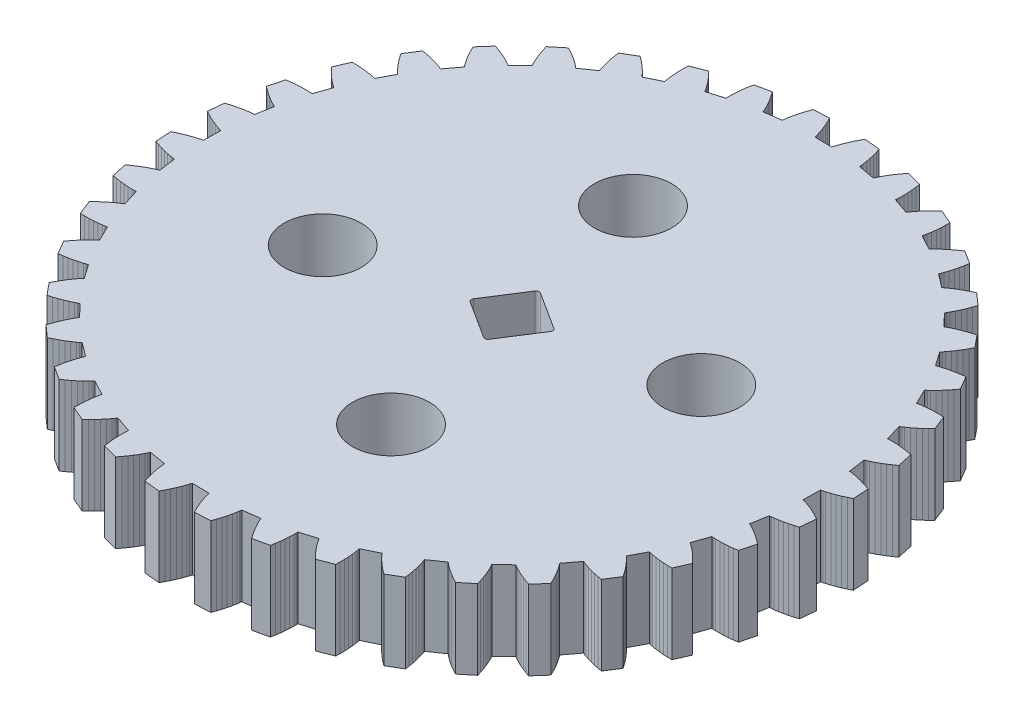
SolidWorks part; units mm, degrees
ref_plane "Front Plane" through (0, 0, 0) normal (0, 0, 1) x (1, 0, 0)
ref_plane "Top Plane" through (0, 0, 0) normal (0, 1, 0) x (1, 0, 0)
ref_plane "Right Plane" through (0, 0, 0) normal (1, 0, 0) x (0, 0, -1)
sketch "Sketch2" plane through (0, 0, 0) normal (0, 1, 0) x (1, 0, 0)
  line L0 (1.6245, 18.6336) -> (1.5605, 18.6409)
  line L1 (1.5605, 18.6409) -> (1.4964, 18.6492)
  line L2 (1.4964, 18.6492) -> (1.3679, 18.6686)
  line L3 (1.3679, 18.6686) -> (1.1102, 18.7172)
  line L4 (1.1102, 18.7172) -> (0.8515, 18.7777)
  line L5 (0.8515, 18.7777) -> (0.5922, 18.8492)
  line L6 (0.5922, 18.8492) -> (0.3324, 18.931)
  line L7 (0.3324, 18.931) -> (0.0723, 19.0226)
  line L8 (0.0723, 19.0226) -> (0.0134, 20.0093)
  line L9 (0.0134, 20.0093) -> (0.2607, 20.1312)
  line L10 (0.2607, 20.1312) -> (0.5089, 20.2434)
  line L11 (0.5089, 20.2434) -> (0.7578, 20.3453)
  line L12 (0.7578, 20.3453) -> (1.0074, 20.4362)
  line L13 (1.0074, 20.4362) -> (1.2576, 20.5151)
  line L14 (1.2576, 20.5151) -> (1.3828, 20.5496)
  line L15 (1.3828, 20.5496) -> (1.4455, 20.5655)
  line L16 (1.4455, 20.5655) -> (1.5081, 20.5804)
  line L17 (1.5081, 20.5804) -> (1.5283, 21.6521)
  line L18 (1.5283, 21.6521) -> (1.4663, 21.6694)
  line L19 (1.4663, 21.6694) -> (1.4043, 21.6877)
  line L20 (1.4043, 21.6877) -> (1.2804, 21.7268)
  line L21 (1.2804, 21.7268) -> (1.0334, 21.8151)
  line L22 (1.0334, 21.8151) -> (0.7874, 21.9154)
  line L23 (0.7874, 21.9154) -> (0.5425, 22.0266)
  line L24 (0.5425, 22.0266) -> (0.2987, 22.1481)
  line L25 (0.2987, 22.1481) -> (0.0561, 22.2792)
  line L26 (0.0561, 22.2792) -> (0.1523, 23.263)
  line L27 (0.1523, 23.263) -> (0.4156, 23.3447)
  line L28 (0.4156, 23.3447) -> (0.6783, 23.4167)
  line L29 (0.6783, 23.4167) -> (0.9401, 23.4783)
  line L30 (0.9401, 23.4783) -> (1.2009, 23.5291)
  line L31 (1.2009, 23.5291) -> (1.4603, 23.5679)
  line L32 (1.4603, 23.5679) -> (1.5894, 23.5824)
  line L33 (1.5894, 23.5824) -> (1.6537, 23.5883)
  line L34 (1.6537, 23.5883) -> (1.718, 23.5932)
  line L35 (1.718, 23.5932) -> (1.9056, 24.6486)
  line L36 (1.9056, 24.6486) -> (1.847, 24.6754)
  line L37 (1.847, 24.6754) -> (1.7886, 24.7031)
  line L38 (1.7886, 24.7031) -> (1.6724, 24.7612)
  line L39 (1.6724, 24.7612) -> (1.4423, 24.887)
  line L40 (1.4423, 24.887) -> (1.215, 25.0245)
  line L41 (1.215, 25.0245) -> (0.9905, 25.1727)
  line L42 (0.9905, 25.1727) -> (0.7687, 25.3307)
  line L43 (0.7687, 25.3307) -> (0.5496, 25.4982)
  line L44 (0.5496, 25.4982) -> (0.7984, 26.4549)
  line L45 (0.7984, 26.4549) -> (1.0713, 26.4944)
  line L46 (1.0713, 26.4944) -> (1.342, 26.5243)
  line L47 (1.342, 26.5243) -> (1.6103, 26.5443)
  line L48 (1.6103, 26.5443) -> (1.8758, 26.5537)
  line L49 (1.8758, 26.5537) -> (2.1381, 26.5514)
  line L50 (2.1381, 26.5514) -> (2.2678, 26.5455)
  line L51 (2.2678, 26.5455) -> (2.3323, 26.5413)
  line L52 (2.3323, 26.5413) -> (2.3965, 26.5361)
  line L53 (2.3965, 26.5361) -> (2.7469, 27.5491)
  line L54 (2.7469, 27.5491) -> (2.6932, 27.5847)
  line L55 (2.6932, 27.5847) -> (2.6399, 27.6212)
  line L56 (2.6399, 27.6212) -> (2.5342, 27.6968)
  line L57 (2.5342, 27.6968) -> (2.3266, 27.8571)
  line L58 (2.3266, 27.8571) -> (2.1237, 28.0284)
  line L59 (2.1237, 28.0284) -> (1.9251, 28.2099)
  line L60 (1.9251, 28.2099) -> (1.7307, 28.4007)
  line L61 (1.7307, 28.4007) -> (1.5406, 28.6004)
  line L62 (1.5406, 28.6004) -> (1.936, 29.5064)
  line L63 (1.936, 29.5064) -> (2.2117, 29.5027)
  line L64 (2.2117, 29.5027) -> (2.4838, 29.49)
  line L65 (2.4838, 29.49) -> (2.7519, 29.4677)
  line L66 (2.7519, 29.4677) -> (3.0155, 29.4354)
  line L67 (3.0155, 29.4354) -> (3.2742, 29.3922)
  line L68 (3.2742, 29.3922) -> (3.4015, 29.3661)
  line L69 (3.4015, 29.3661) -> (3.4645, 29.3518)
  line L70 (3.4645, 29.3518) -> (3.5271, 29.3366)
  line L71 (3.5271, 29.3366) -> (4.0316, 30.2823)
  line L72 (4.0316, 30.2823) -> (3.9842, 30.3259)
  line L73 (3.9842, 30.3259) -> (3.9372, 30.3703)
  line L74 (3.9372, 30.3703) -> (3.8447, 30.4614)
  line L75 (3.8447, 30.4614) -> (3.6647, 30.6522)
  line L76 (3.6647, 30.6522) -> (3.491, 30.8533)
  line L77 (3.491, 30.8533) -> (3.3233, 31.0635)
  line L78 (3.3233, 31.0635) -> (3.1612, 31.2824)
  line L79 (3.1612, 31.2824) -> (3.0046, 31.5094)
  line L80 (3.0046, 31.5094) -> (3.5369, 32.3423)
  line L81 (3.5369, 32.3423) -> (3.8086, 32.2956)
  line L82 (3.8086, 32.2956) -> (4.0754, 32.2404)
  line L83 (4.0754, 32.2404) -> (4.3367, 32.1765)
  line L84 (4.3367, 32.1765) -> (4.592, 32.1034)
  line L85 (4.592, 32.1034) -> (4.8408, 32.0202)
  line L86 (4.8408, 32.0202) -> (4.9624, 31.9745)
  line L87 (4.9624, 31.9745) -> (5.0224, 31.9505)
  line L88 (5.0224, 31.9505) -> (5.0819, 31.9258)
  line L89 (5.0819, 31.9258) -> (5.7281, 32.7809)
  line L90 (5.7281, 32.7809) -> (5.6881, 32.8314)
  line L91 (5.6881, 32.8314) -> (5.6486, 32.8826)
  line L92 (5.6486, 32.8826) -> (5.5715, 32.9871)
  line L93 (5.5715, 32.9871) -> (5.4236, 33.2037)
  line L94 (5.4236, 33.2037) -> (5.2835, 33.4294)
  line L95 (5.2835, 33.4294) -> (5.1507, 33.6633)
  line L96 (5.1507, 33.6633) -> (5.0248, 33.9049)
  line L97 (5.0248, 33.9049) -> (4.9057, 34.1535)
  line L98 (4.9057, 34.1535) -> (5.5617, 34.893)
  line L99 (5.5617, 34.893) -> (5.8228, 34.8043)
  line L100 (5.8228, 34.8043) -> (6.0776, 34.7081)
  line L101 (6.0776, 34.7081) -> (6.3257, 34.6041)
  line L102 (6.3257, 34.6041) -> (6.5665, 34.4919)
  line L103 (6.5665, 34.4919) -> (6.7992, 34.3708)
  line L104 (6.7992, 34.3708) -> (6.9121, 34.3067)
  line L105 (6.9121, 34.3067) -> (6.9676, 34.2736)
  line L106 (6.9676, 34.2736) -> (7.0225, 34.2398)
  line L107 (7.0225, 34.2398) -> (7.7946, 34.9834)
  line L108 (7.7946, 34.9834) -> (7.7629, 35.0395)
  line L109 (7.7629, 35.0395) -> (7.732, 35.0962)
  line L110 (7.732, 35.0962) -> (7.6721, 35.2115)
  line L111 (7.6721, 35.2115) -> (7.5599, 35.4485)
  line L112 (7.5599, 35.4485) -> (7.4569, 35.6934)
  line L113 (7.4569, 35.6934) -> (7.3623, 35.9452)
  line L114 (7.3623, 35.9452) -> (7.2758, 36.2035)
  line L115 (7.2758, 36.2035) -> (7.197, 36.4677)
  line L116 (7.197, 36.4677) -> (7.9606, 37.0954)
  line L117 (7.9606, 37.0954) -> (8.2046, 36.967)
  line L118 (8.2046, 36.967) -> (8.4413, 36.8321)
  line L119 (8.4413, 36.8321) -> (8.67, 36.6906)
  line L120 (8.67, 36.6906) -> (8.8903, 36.5421)
  line L121 (8.8903, 36.5421) -> (9.1012, 36.3861)
  line L122 (9.1012, 36.3861) -> (9.2027, 36.3051)
  line L123 (9.2027, 36.3051) -> (9.2524, 36.2638)
  line L124 (9.2524, 36.2638) -> (9.3013, 36.2218)
  line L125 (9.3013, 36.2218) -> (10.1802, 36.8354)
  line L126 (10.1802, 36.8354) -> (10.1577, 36.8958)
  line L127 (10.1577, 36.8958) -> (10.136, 36.9567)
  line L128 (10.136, 36.9567) -> (10.0949, 37.0799)
  line L129 (10.0949, 37.0799) -> (10.0212, 37.3316)
  line L130 (10.0212, 37.3316) -> (9.9577, 37.5895)
  line L131 (9.9577, 37.5895) -> (9.9037, 37.8531)
  line L132 (9.9037, 37.8531) -> (9.8586, 38.1217)
  line L133 (9.8586, 38.1217) -> (9.8221, 38.395)
  line L134 (9.8221, 38.395) -> (10.6745, 38.8955)
  line L135 (10.6745, 38.8955) -> (10.8954, 38.7305)
  line L136 (10.8954, 38.7305) -> (11.1081, 38.5603)
  line L137 (11.1081, 38.5603) -> (11.3119, 38.3847)
  line L138 (11.3119, 38.3847) -> (11.5062, 38.2036)
  line L139 (11.5062, 38.2036) -> (11.6901, 38.0165)
  line L140 (11.6901, 38.0165) -> (11.7777, 37.9206)
  line L141 (11.7777, 37.9206) -> (11.8203, 37.872)
  line L142 (11.8203, 37.872) -> (11.862, 37.8229)
  line L143 (11.862, 37.8229) -> (12.8261, 38.2915)
  line L144 (12.8261, 38.2915) -> (12.8133, 38.3546)
  line L145 (12.8133, 38.3546) -> (12.8014, 38.4181)
  line L146 (12.8014, 38.4181) -> (12.7801, 38.5463)
  line L147 (12.7801, 38.5463) -> (12.7467, 38.8064)
  line L148 (12.7467, 38.8064) -> (12.7243, 39.0711)
  line L149 (12.7243, 39.0711) -> (12.7122, 39.3399)
  line L150 (12.7122, 39.3399) -> (12.7097, 39.6122)
  line L151 (12.7097, 39.6122) -> (12.7164, 39.8879)
  line L152 (12.7164, 39.8879) -> (13.6366, 40.2489)
  line L153 (13.6366, 40.2489) -> (13.829, 40.0513)
  line L154 (13.829, 40.0513) -> (14.0124, 39.8499)
  line L155 (14.0124, 39.8499) -> (14.1862, 39.6446)
  line L156 (14.1862, 39.6446) -> (14.3498, 39.4353)
  line L157 (14.3498, 39.4353) -> (14.5022, 39.2218)
  line L158 (14.5022, 39.2218) -> (14.5737, 39.1134)
  line L159 (14.5737, 39.1134) -> (14.6082, 39.0587)
  line L160 (14.6082, 39.0587) -> (14.6417, 39.0037)
  line L161 (14.6417, 39.0037) -> (15.6672, 39.3157)
  line L162 (15.6672, 39.3157) -> (15.6645, 39.3801)
  line L163 (15.6645, 39.3801) -> (15.6626, 39.4447)
  line L164 (15.6626, 39.4447) -> (15.6616, 39.5746)
  line L165 (15.6616, 39.5746) -> (15.6693, 39.8367)
  line L166 (15.6693, 39.8367) -> (15.6886, 40.1017)
  line L167 (15.6886, 40.1017) -> (15.7187, 40.369)
  line L168 (15.7187, 40.369) -> (15.7589, 40.6384)
  line L169 (15.7589, 40.6384) -> (15.8086, 40.9096)
  line L170 (15.8086, 40.9096) -> (16.774, 41.1222)
  line L171 (16.774, 41.1222) -> (16.9331, 40.897)
  line L172 (16.9331, 40.897) -> (17.0827, 40.6694)
  line L173 (17.0827, 40.6694) -> (17.2223, 40.4394)
  line L174 (17.2223, 40.4394) -> (17.3511, 40.2071)
  line L175 (17.3511, 40.2071) -> (17.4682, 39.9724)
  line L176 (17.4682, 39.9724) -> (17.5219, 39.8541)
  line L177 (17.5219, 39.8541) -> (17.5474, 39.7947)
  line L178 (17.5474, 39.7947) -> (17.5719, 39.7352)
  line L179 (17.5719, 39.7352) -> (18.6336, 39.8829)
  line L180 (18.6336, 39.8829) -> (18.6409, 39.9469)
  line L181 (18.6409, 39.9469) -> (18.6492, 40.011)
  line L182 (18.6492, 40.011) -> (18.6686, 40.1394)
  line L183 (18.6686, 40.1394) -> (18.7172, 40.3972)
  line L184 (18.7172, 40.3972) -> (18.7777, 40.6558)
  line L185 (18.7777, 40.6558) -> (18.8492, 40.9151)
  line L186 (18.8492, 40.9151) -> (18.931, 41.1749)
  line L187 (18.931, 41.1749) -> (19.0226, 41.435)
  line L188 (19.0226, 41.435) -> (20.0093, 41.494)
  line L189 (20.0093, 41.494) -> (20.1312, 41.2467)
  line L190 (20.1312, 41.2467) -> (20.2434, 40.9985)
  line L191 (20.2434, 40.9985) -> (20.3453, 40.7495)
  line L192 (20.3453, 40.7495) -> (20.4362, 40.4999)
  line L193 (20.4362, 40.4999) -> (20.5151, 40.2498)
  line L194 (20.5151, 40.2498) -> (20.5496, 40.1245)
  line L195 (20.5496, 40.1245) -> (20.5655, 40.0619)
  line L196 (20.5655, 40.0619) -> (20.5804, 39.9992)
  line L197 (20.5804, 39.9992) -> (21.6521, 39.979)
  line L198 (21.6521, 39.979) -> (21.6694, 40.0411)
  line L199 (21.6694, 40.0411) -> (21.6877, 40.1031)
  line L200 (21.6877, 40.1031) -> (21.7268, 40.2269)
  line L201 (21.7268, 40.2269) -> (21.8151, 40.4739)
  line L202 (21.8151, 40.4739) -> (21.9154, 40.7199)
  line L203 (21.9154, 40.7199) -> (22.0266, 40.9648)
  line L204 (22.0266, 40.9648) -> (22.1481, 41.2086)
  line L205 (22.1481, 41.2086) -> (22.2792, 41.4512)
  line L206 (22.2792, 41.4512) -> (23.263, 41.3551)
  line L207 (23.263, 41.3551) -> (23.3447, 41.0917)
  line L208 (23.3447, 41.0917) -> (23.4167, 40.829)
  line L209 (23.4167, 40.829) -> (23.4783, 40.5672)
  line L210 (23.4783, 40.5672) -> (23.5291, 40.3064)
  line L211 (23.5291, 40.3064) -> (23.5679, 40.047)
  line L212 (23.5679, 40.047) -> (23.5824, 39.918)
  line L213 (23.5824, 39.918) -> (23.5883, 39.8536)
  line L214 (23.5883, 39.8536) -> (23.5932, 39.7894)
  line L215 (23.5932, 39.7894) -> (24.6486, 39.6018)
  line L216 (24.6486, 39.6018) -> (24.6754, 39.6604)
  line L217 (24.6754, 39.6604) -> (24.7031, 39.7188)
  line L218 (24.7031, 39.7188) -> (24.7612, 39.8349)
  line L219 (24.7612, 39.8349) -> (24.887, 40.0651)
  line L220 (24.887, 40.0651) -> (25.0245, 40.2923)
  line L221 (25.0245, 40.2923) -> (25.1727, 40.5169)
  line L222 (25.1727, 40.5169) -> (25.3307, 40.7387)
  line L223 (25.3307, 40.7387) -> (25.4982, 40.9577)
  line L224 (25.4982, 40.9577) -> (26.4549, 40.7089)
  line L225 (26.4549, 40.7089) -> (26.4944, 40.436)
  line L226 (26.4944, 40.436) -> (26.5243, 40.1653)
  line L227 (26.5243, 40.1653) -> (26.5443, 39.897)
  line L228 (26.5443, 39.897) -> (26.5537, 39.6315)
  line L229 (26.5537, 39.6315) -> (26.5514, 39.3693)
  line L230 (26.5514, 39.3693) -> (26.5455, 39.2395)
  line L231 (26.5455, 39.2395) -> (26.5413, 39.175)
  line L232 (26.5413, 39.175) -> (26.5361, 39.1108)
  line L233 (26.5361, 39.1108) -> (27.5491, 38.7604)
  line L234 (27.5491, 38.7604) -> (27.5847, 38.8141)
  line L235 (27.5847, 38.8141) -> (27.6212, 38.8674)
  line L236 (27.6212, 38.8674) -> (27.6968, 38.9731)
  line L237 (27.6968, 38.9731) -> (27.8571, 39.1807)
  line L238 (27.8571, 39.1807) -> (28.0284, 39.3837)
  line L239 (28.0284, 39.3837) -> (28.2099, 39.5823)
  line L240 (28.2099, 39.5823) -> (28.4007, 39.7766)
  line L241 (28.4007, 39.7766) -> (28.6004, 39.9668)
  line L242 (28.6004, 39.9668) -> (29.5064, 39.5714)
  line L243 (29.5064, 39.5714) -> (29.5027, 39.2956)
  line L244 (29.5027, 39.2956) -> (29.49, 39.0236)
  line L245 (29.49, 39.0236) -> (29.4677, 38.7555)
  line L246 (29.4677, 38.7555) -> (29.4354, 38.4918)
  line L247 (29.4354, 38.4918) -> (29.3922, 38.2331)
  line L248 (29.3922, 38.2331) -> (29.3661, 38.1059)
  line L249 (29.3661, 38.1059) -> (29.3518, 38.0428)
  line L250 (29.3518, 38.0428) -> (29.3366, 37.9802)
  line L251 (29.3366, 37.9802) -> (30.2823, 37.4757)
  line L252 (30.2823, 37.4757) -> (30.3259, 37.5231)
  line L253 (30.3259, 37.5231) -> (30.3703, 37.5701)
  line L254 (30.3703, 37.5701) -> (30.4614, 37.6626)
  line L255 (30.4614, 37.6626) -> (30.6522, 37.8426)
  line L256 (30.6522, 37.8426) -> (30.8533, 38.0163)
  line L257 (30.8533, 38.0163) -> (31.0635, 38.184)
  line L258 (31.0635, 38.184) -> (31.2824, 38.3462)
  line L259 (31.2824, 38.3462) -> (31.5094, 38.5027)
  line L260 (31.5094, 38.5027) -> (32.3423, 37.9704)
  line L261 (32.3423, 37.9704) -> (32.2956, 37.6987)
  line L262 (32.2956, 37.6987) -> (32.2404, 37.432)
  line L263 (32.2404, 37.432) -> (32.1765, 37.1707)
  line L264 (32.1765, 37.1707) -> (32.1034, 36.9153)
  line L265 (32.1034, 36.9153) -> (32.0202, 36.6666)
  line L266 (32.0202, 36.6666) -> (31.9745, 36.545)
  line L267 (31.9745, 36.545) -> (31.9505, 36.4849)
  line L268 (31.9505, 36.4849) -> (31.9258, 36.4255)
  line L269 (31.9258, 36.4255) -> (32.7809, 35.7792)
  line L270 (32.7809, 35.7792) -> (32.8314, 35.8192)
  line L271 (32.8314, 35.8192) -> (32.8826, 35.8587)
  line L272 (32.8826, 35.8587) -> (32.9871, 35.9358)
  line L273 (32.9871, 35.9358) -> (33.2037, 36.0838)
  line L274 (33.2037, 36.0838) -> (33.4294, 36.2238)
  line L275 (33.4294, 36.2238) -> (33.6633, 36.3566)
  line L276 (33.6633, 36.3566) -> (33.9049, 36.4825)
  line L277 (33.9049, 36.4825) -> (34.1535, 36.6016)
  line L278 (34.1535, 36.6016) -> (34.893, 35.9456)
  line L279 (34.893, 35.9456) -> (34.8043, 35.6845)
  line L280 (34.8043, 35.6845) -> (34.7081, 35.4297)
  line L281 (34.7081, 35.4297) -> (34.6041, 35.1816)
  line L282 (34.6041, 35.1816) -> (34.4919, 34.9408)
  line L283 (34.4919, 34.9408) -> (34.3708, 34.7082)
  line L284 (34.3708, 34.7082) -> (34.3067, 34.5952)
  line L285 (34.3067, 34.5952) -> (34.2736, 34.5397)
  line L286 (34.2736, 34.5397) -> (34.2398, 34.4848)
  line L287 (34.2398, 34.4848) -> (34.9834, 33.7127)
  line L288 (34.9834, 33.7127) -> (35.0395, 33.7444)
  line L289 (35.0395, 33.7444) -> (35.0962, 33.7753)
  line L290 (35.0962, 33.7753) -> (35.2115, 33.8352)
  line L291 (35.2115, 33.8352) -> (35.4485, 33.9474)
  line L292 (35.4485, 33.9474) -> (35.6934, 34.0504)
  line L293 (35.6934, 34.0504) -> (35.9452, 34.145)
  line L294 (35.9452, 34.145) -> (36.2035, 34.2315)
  line L295 (36.2035, 34.2315) -> (36.4677, 34.3103)
  line L296 (36.4677, 34.3103) -> (37.0954, 33.5467)
  line L297 (37.0954, 33.5467) -> (36.967, 33.3027)
  line L298 (36.967, 33.3027) -> (36.8321, 33.0661)
  line L299 (36.8321, 33.0661) -> (36.6906, 32.8373)
  line L300 (36.6906, 32.8373) -> (36.5421, 32.617)
  line L301 (36.5421, 32.617) -> (36.3861, 32.4062)
  line L302 (36.3861, 32.4062) -> (36.3051, 32.3047)
  line L303 (36.3051, 32.3047) -> (36.2638, 32.255)
  line L304 (36.2638, 32.255) -> (36.2218, 32.2061)
  line L305 (36.2218, 32.2061) -> (36.8354, 31.3272)
  line L306 (36.8354, 31.3272) -> (36.8958, 31.3497)
  line L307 (36.8958, 31.3497) -> (36.9567, 31.3713)
  line L308 (36.9567, 31.3713) -> (37.0799, 31.4124)
  line L309 (37.0799, 31.4124) -> (37.3316, 31.4862)
  line L310 (37.3316, 31.4862) -> (37.5895, 31.5497)
  line L311 (37.5895, 31.5497) -> (37.8531, 31.6037)
  line L312 (37.8531, 31.6037) -> (38.1217, 31.6487)
  line L313 (38.1217, 31.6487) -> (38.395, 31.6852)
  line L314 (38.395, 31.6852) -> (38.8955, 30.8328)
  line L315 (38.8955, 30.8328) -> (38.7305, 30.6119)
  line L316 (38.7305, 30.6119) -> (38.5603, 30.3993)
  line L317 (38.5603, 30.3993) -> (38.3847, 30.1955)
  line L318 (38.3847, 30.1955) -> (38.2036, 30.0011)
  line L319 (38.2036, 30.0011) -> (38.0165, 29.8173)
  line L320 (38.0165, 29.8173) -> (37.9206, 29.7297)
  line L321 (37.9206, 29.7297) -> (37.872, 29.6871)
  line L322 (37.872, 29.6871) -> (37.8229, 29.6453)
  line L323 (37.8229, 29.6453) -> (38.2915, 28.6812)
  line L324 (38.2915, 28.6812) -> (38.3546, 28.694)
  line L325 (38.3546, 28.694) -> (38.4181, 28.7059)
  line L326 (38.4181, 28.7059) -> (38.5463, 28.7272)
  line L327 (38.5463, 28.7272) -> (38.8064, 28.7607)
  line L328 (38.8064, 28.7607) -> (39.0711, 28.783)
  line L329 (39.0711, 28.783) -> (39.3399, 28.7951)
  line L330 (39.3399, 28.7951) -> (39.6122, 28.7976)
  line L331 (39.6122, 28.7976) -> (39.8879, 28.7909)
  line L332 (39.8879, 28.7909) -> (40.2489, 27.8707)
  line L333 (40.2489, 27.8707) -> (40.0513, 27.6783)
  line L334 (40.0513, 27.6783) -> (39.8499, 27.495)
  line L335 (39.8499, 27.495) -> (39.6446, 27.3211)
  line L336 (39.6446, 27.3211) -> (39.4353, 27.1575)
  line L337 (39.4353, 27.1575) -> (39.2218, 27.0052)
  line L338 (39.2218, 27.0052) -> (39.1134, 26.9337)
  line L339 (39.1134, 26.9337) -> (39.0587, 26.8992)
  line L340 (39.0587, 26.8992) -> (39.0037, 26.8656)
  line L341 (39.0037, 26.8656) -> (39.3157, 25.8401)
  line L342 (39.3157, 25.8401) -> (39.3801, 25.8429)
  line L343 (39.3801, 25.8429) -> (39.4447, 25.8447)
  line L344 (39.4447, 25.8447) -> (39.5746, 25.8457)
  line L345 (39.5746, 25.8457) -> (39.8367, 25.838)
  line L346 (39.8367, 25.838) -> (40.1017, 25.8187)
  line L347 (40.1017, 25.8187) -> (40.369, 25.7886)
  line L348 (40.369, 25.7886) -> (40.6384, 25.7485)
  line L349 (40.6384, 25.7485) -> (40.9096, 25.6987)
  line L350 (40.9096, 25.6987) -> (41.1222, 24.7333)
  line L351 (41.1222, 24.7333) -> (40.897, 24.5743)
  line L352 (40.897, 24.5743) -> (40.6694, 24.4246)
  line L353 (40.6694, 24.4246) -> (40.4394, 24.2851)
  line L354 (40.4394, 24.2851) -> (40.2071, 24.1562)
  line L355 (40.2071, 24.1562) -> (39.9724, 24.0391)
  line L356 (39.9724, 24.0391) -> (39.8541, 23.9855)
  line L357 (39.8541, 23.9855) -> (39.7947, 23.96)
  line L358 (39.7947, 23.96) -> (39.7352, 23.9354)
  line L359 (39.7352, 23.9354) -> (39.8829, 22.8738)
  line L360 (39.8829, 22.8738) -> (39.9469, 22.8664)
  line L361 (39.9469, 22.8664) -> (40.011, 22.8581)
  line L362 (40.011, 22.8581) -> (40.1394, 22.8388)
  line L363 (40.1394, 22.8388) -> (40.3972, 22.7902)
  line L364 (40.3972, 22.7902) -> (40.6558, 22.7296)
  line L365 (40.6558, 22.7296) -> (40.9151, 22.6581)
  line L366 (40.9151, 22.6581) -> (41.1749, 22.5763)
  line L367 (41.1749, 22.5763) -> (41.435, 22.4847)
  line L368 (41.435, 22.4847) -> (41.494, 21.498)
  line L369 (41.494, 21.498) -> (41.2467, 21.3761)
  line L370 (41.2467, 21.3761) -> (40.9985, 21.264)
  line L371 (40.9985, 21.264) -> (40.7495, 21.1621)
  line L372 (40.7495, 21.1621) -> (40.4999, 21.0711)
  line L373 (40.4999, 21.0711) -> (40.2498, 20.9922)
  line L374 (40.2498, 20.9922) -> (40.1245, 20.9577)
  line L375 (40.1245, 20.9577) -> (40.0619, 20.9418)
  line L376 (40.0619, 20.9418) -> (39.9992, 20.9269)
  line L377 (39.9992, 20.9269) -> (39.979, 19.8552)
  line L378 (39.979, 19.8552) -> (40.0411, 19.8379)
  line L379 (40.0411, 19.8379) -> (40.1031, 19.8197)
  line L380 (40.1031, 19.8197) -> (40.2269, 19.7805)
  line L381 (40.2269, 19.7805) -> (40.4739, 19.6922)
  line L382 (40.4739, 19.6922) -> (40.7199, 19.5919)
  line L383 (40.7199, 19.5919) -> (40.9648, 19.4807)
  line L384 (40.9648, 19.4807) -> (41.2086, 19.3593)
  line L385 (41.2086, 19.3593) -> (41.4512, 19.2281)
  line L386 (41.4512, 19.2281) -> (41.3551, 18.2443)
  line L387 (41.3551, 18.2443) -> (41.0917, 18.1626)
  line L388 (41.0917, 18.1626) -> (40.829, 18.0907)
  line L389 (40.829, 18.0907) -> (40.5672, 18.029)
  line L390 (40.5672, 18.029) -> (40.3064, 17.9782)
  line L391 (40.3064, 17.9782) -> (40.047, 17.9394)
  line L392 (40.047, 17.9394) -> (39.918, 17.9249)
  line L393 (39.918, 17.9249) -> (39.8536, 17.919)
  line L394 (39.8536, 17.919) -> (39.7894, 17.9141)
  line L395 (39.7894, 17.9141) -> (39.6018, 16.8588)
  line L396 (39.6018, 16.8588) -> (39.6604, 16.832)
  line L397 (39.6604, 16.832) -> (39.7188, 16.8043)
  line L398 (39.7188, 16.8043) -> (39.8349, 16.7462)
  line L399 (39.8349, 16.7462) -> (40.0651, 16.6203)
  line L400 (40.0651, 16.6203) -> (40.2923, 16.4828)
  line L401 (40.2923, 16.4828) -> (40.5169, 16.3347)
  line L402 (40.5169, 16.3347) -> (40.7387, 16.1766)
  line L403 (40.7387, 16.1766) -> (40.9577, 16.0091)
  line L404 (40.9577, 16.0091) -> (40.7089, 15.0525)
  line L405 (40.7089, 15.0525) -> (40.436, 15.013)
  line L406 (40.436, 15.013) -> (40.1653, 14.983)
  line L407 (40.1653, 14.983) -> (39.897, 14.963)
  line L408 (39.897, 14.963) -> (39.6315, 14.9537)
  line L409 (39.6315, 14.9537) -> (39.3693, 14.9559)
  line L410 (39.3693, 14.9559) -> (39.2395, 14.9618)
  line L411 (39.2395, 14.9618) -> (39.175, 14.966)
  line L412 (39.175, 14.966) -> (39.1108, 14.9712)
  line L413 (39.1108, 14.9712) -> (38.7604, 13.9582)
  line L414 (38.7604, 13.9582) -> (38.8141, 13.9226)
  line L415 (38.8141, 13.9226) -> (38.8674, 13.8861)
  line L416 (38.8674, 13.8861) -> (38.9731, 13.8105)
  line L417 (38.9731, 13.8105) -> (39.1807, 13.6503)
  line L418 (39.1807, 13.6503) -> (39.3837, 13.4789)
  line L419 (39.3837, 13.4789) -> (39.5823, 13.2974)
  line L420 (39.5823, 13.2974) -> (39.7766, 13.1066)
  line L421 (39.7766, 13.1066) -> (39.9668, 12.9069)
  line L422 (39.9668, 12.9069) -> (39.5714, 12.001)
  line L423 (39.5714, 12.001) -> (39.2956, 12.0046)
  line L424 (39.2956, 12.0046) -> (39.0236, 12.0174)
  line L425 (39.0236, 12.0174) -> (38.7555, 12.0396)
  line L426 (38.7555, 12.0396) -> (38.4918, 12.0719)
  line L427 (38.4918, 12.0719) -> (38.2331, 12.1152)
  line L428 (38.2331, 12.1152) -> (38.1059, 12.1413)
  line L429 (38.1059, 12.1413) -> (38.0428, 12.1556)
  line L430 (38.0428, 12.1556) -> (37.9802, 12.1707)
  line L431 (37.9802, 12.1707) -> (37.4757, 11.225)
  line L432 (37.4757, 11.225) -> (37.5231, 11.1814)
  line L433 (37.5231, 11.1814) -> (37.5701, 11.137)
  line L434 (37.5701, 11.137) -> (37.6626, 11.0459)
  line L435 (37.6626, 11.0459) -> (37.8426, 10.8551)
  line L436 (37.8426, 10.8551) -> (38.0163, 10.6541)
  line L437 (38.0163, 10.6541) -> (38.184, 10.4438)
  line L438 (38.184, 10.4438) -> (38.3462, 10.2249)
  line L439 (38.3462, 10.2249) -> (38.5027, 9.9979)
  line L440 (38.5027, 9.9979) -> (37.9704, 9.165)
  line L441 (37.9704, 9.165) -> (37.6987, 9.2118)
  line L442 (37.6987, 9.2118) -> (37.432, 9.2669)
  line L443 (37.432, 9.2669) -> (37.1707, 9.3308)
  line L444 (37.1707, 9.3308) -> (36.9153, 9.404)
  line L445 (36.9153, 9.404) -> (36.6666, 9.4871)
  line L446 (36.6666, 9.4871) -> (36.545, 9.5328)
  line L447 (36.545, 9.5328) -> (36.4849, 9.5568)
  line L448 (36.4849, 9.5568) -> (36.4255, 9.5816)
  line L449 (36.4255, 9.5816) -> (35.7792, 8.7264)
  line L450 (35.7792, 8.7264) -> (35.8192, 8.676)
  line L451 (35.8192, 8.676) -> (35.8587, 8.6248)
  line L452 (35.8587, 8.6248) -> (35.9358, 8.5203)
  line L453 (35.9358, 8.5203) -> (36.0838, 8.3037)
  line L454 (36.0838, 8.3037) -> (36.2238, 8.078)
  line L455 (36.2238, 8.078) -> (36.3566, 7.844)
  line L456 (36.3566, 7.844) -> (36.4825, 7.6025)
  line L457 (36.4825, 7.6025) -> (36.6016, 7.3538)
  line L458 (36.6016, 7.3538) -> (35.9456, 6.6144)
  line L459 (35.9456, 6.6144) -> (35.6845, 6.7031)
  line L460 (35.6845, 6.7031) -> (35.4297, 6.7993)
  line L461 (35.4297, 6.7993) -> (35.1816, 6.9032)
  line L462 (35.1816, 6.9032) -> (34.9408, 7.0155)
  line L463 (34.9408, 7.0155) -> (34.7082, 7.1365)
  line L464 (34.7082, 7.1365) -> (34.5952, 7.2007)
  line L465 (34.5952, 7.2007) -> (34.5397, 7.2337)
  line L466 (34.5397, 7.2337) -> (34.4848, 7.2675)
  line L467 (34.4848, 7.2675) -> (33.7127, 6.524)
  line L468 (33.7127, 6.524) -> (33.7444, 6.4679)
  line L469 (33.7444, 6.4679) -> (33.7753, 6.4111)
  line L470 (33.7753, 6.4111) -> (33.8352, 6.2959)
  line L471 (33.8352, 6.2959) -> (33.9474, 6.0588)
  line L472 (33.9474, 6.0588) -> (34.0504, 5.8139)
  line L473 (34.0504, 5.8139) -> (34.145, 5.5621)
  line L474 (34.145, 5.5621) -> (34.2315, 5.3038)
  line L475 (34.2315, 5.3038) -> (34.3103, 5.0396)
  line L476 (34.3103, 5.0396) -> (33.5467, 4.4119)
  line L477 (33.5467, 4.4119) -> (33.3027, 4.5404)
  line L478 (33.3027, 4.5404) -> (33.0661, 4.6752)
  line L479 (33.0661, 4.6752) -> (32.8373, 4.8167)
  line L480 (32.8373, 4.8167) -> (32.617, 4.9652)
  line L481 (32.617, 4.9652) -> (32.4062, 5.1212)
  line L482 (32.4062, 5.1212) -> (32.3047, 5.2022)
  line L483 (32.3047, 5.2022) -> (32.255, 5.2436)
  line L484 (32.255, 5.2436) -> (32.2061, 5.2855)
  line L485 (32.2061, 5.2855) -> (31.3272, 4.6719)
  line L486 (31.3272, 4.6719) -> (31.3497, 4.6116)
  line L487 (31.3497, 4.6116) -> (31.3713, 4.5507)
  line L488 (31.3713, 4.5507) -> (31.4124, 4.4275)
  line L489 (31.4124, 4.4275) -> (31.4862, 4.1757)
  line L490 (31.4862, 4.1757) -> (31.5497, 3.9178)
  line L491 (31.5497, 3.9178) -> (31.6037, 3.6543)
  line L492 (31.6037, 3.6543) -> (31.6487, 3.3857)
  line L493 (31.6487, 3.3857) -> (31.6852, 3.1123)
  line L494 (31.6852, 3.1123) -> (30.8328, 2.6118)
  line L495 (30.8328, 2.6118) -> (30.6119, 2.7769)
  line L496 (30.6119, 2.7769) -> (30.3993, 2.9471)
  line L497 (30.3993, 2.9471) -> (30.1955, 3.1227)
  line L498 (30.1955, 3.1227) -> (30.0011, 3.3038)
  line L499 (30.0011, 3.3038) -> (29.8173, 3.4908)
  line L500 (29.8173, 3.4908) -> (29.7297, 3.5867)
  line L501 (29.7297, 3.5867) -> (29.6871, 3.6353)
  line L502 (29.6871, 3.6353) -> (29.6453, 3.6844)
  line L503 (29.6453, 3.6844) -> (28.6812, 3.2159)
  line L504 (28.6812, 3.2159) -> (28.694, 3.1527)
  line L505 (28.694, 3.1527) -> (28.7059, 3.0892)
  line L506 (28.7059, 3.0892) -> (28.7272, 2.9611)
  line L507 (28.7272, 2.9611) -> (28.7607, 2.7009)
  line L508 (28.7607, 2.7009) -> (28.783, 2.4362)
  line L509 (28.783, 2.4362) -> (28.7951, 2.1675)
  line L510 (28.7951, 2.1675) -> (28.7976, 1.8951)
  line L511 (28.7976, 1.8951) -> (28.7909, 1.6195)
  line L512 (28.7909, 1.6195) -> (27.8707, 1.2585)
  line L513 (27.8707, 1.2585) -> (27.6783, 1.456)
  line L514 (27.6783, 1.456) -> (27.495, 1.6574)
  line L515 (27.495, 1.6574) -> (27.3211, 1.8627)
  line L516 (27.3211, 1.8627) -> (27.1575, 2.072)
  line L517 (27.1575, 2.072) -> (27.0052, 2.2855)
  line L518 (27.0052, 2.2855) -> (26.9337, 2.3939)
  line L519 (26.9337, 2.3939) -> (26.8992, 2.4486)
  line L520 (26.8992, 2.4486) -> (26.8656, 2.5036)
  line L521 (26.8656, 2.5036) -> (25.8401, 2.1916)
  line L522 (25.8401, 2.1916) -> (25.8429, 2.1273)
  line L523 (25.8429, 2.1273) -> (25.8447, 2.0627)
  line L524 (25.8447, 2.0627) -> (25.8457, 1.9328)
  line L525 (25.8457, 1.9328) -> (25.838, 1.6706)
  line L526 (25.838, 1.6706) -> (25.8187, 1.4057)
  line L527 (25.8187, 1.4057) -> (25.7886, 1.1383)
  line L528 (25.7886, 1.1383) -> (25.7485, 0.8689)
  line L529 (25.7485, 0.8689) -> (25.6987, 0.5977)
  line L530 (25.6987, 0.5977) -> (24.7333, 0.3851)
  line L531 (24.7333, 0.3851) -> (24.5743, 0.6103)
  line L532 (24.5743, 0.6103) -> (24.4246, 0.8379)
  line L533 (24.4246, 0.8379) -> (24.2851, 1.0679)
  line L534 (24.2851, 1.0679) -> (24.1562, 1.3002)
  line L535 (24.1562, 1.3002) -> (24.0391, 1.5349)
  line L536 (24.0391, 1.5349) -> (23.9855, 1.6532)
  line L537 (23.9855, 1.6532) -> (23.96, 1.7126)
  line L538 (23.96, 1.7126) -> (23.9354, 1.7722)
  line L539 (23.9354, 1.7722) -> (22.8738, 1.6245)
  line L540 (22.8738, 1.6245) -> (22.8664, 1.5605)
  line L541 (22.8664, 1.5605) -> (22.8581, 1.4964)
  line L542 (22.8581, 1.4964) -> (22.8388, 1.3679)
  line L543 (22.8388, 1.3679) -> (22.7902, 1.1102)
  line L544 (22.7902, 1.1102) -> (22.7296, 0.8515)
  line L545 (22.7296, 0.8515) -> (22.6581, 0.5922)
  line L546 (22.6581, 0.5922) -> (22.5763, 0.3324)
  line L547 (22.5763, 0.3324) -> (22.4847, 0.0723)
  line L548 (22.4847, 0.0723) -> (21.498, 0.0134)
  line L549 (21.498, 0.0134) -> (21.3761, 0.2607)
  line L550 (21.3761, 0.2607) -> (21.264, 0.5089)
  line L551 (21.264, 0.5089) -> (21.1621, 0.7578)
  line L552 (21.1621, 0.7578) -> (21.0711, 1.0074)
  line L553 (21.0711, 1.0074) -> (20.9922, 1.2576)
  line L554 (20.9922, 1.2576) -> (20.9577, 1.3828)
  line L555 (20.9577, 1.3828) -> (20.9418, 1.4455)
  line L556 (20.9418, 1.4455) -> (20.9269, 1.5081)
  line L557 (20.9269, 1.5081) -> (19.8552, 1.5283)
  line L558 (19.8552, 1.5283) -> (19.8379, 1.4663)
  line L559 (19.8379, 1.4663) -> (19.8197, 1.4043)
  line L560 (19.8197, 1.4043) -> (19.7805, 1.2804)
  line L561 (19.7805, 1.2804) -> (19.6922, 1.0334)
  line L562 (19.6922, 1.0334) -> (19.5919, 0.7874)
  line L563 (19.5919, 0.7874) -> (19.4807, 0.5425)
  line L564 (19.4807, 0.5425) -> (19.3593, 0.2987)
  line L565 (19.3593, 0.2987) -> (19.2281, 0.0561)
  line L566 (19.2281, 0.0561) -> (18.2443, 0.1523)
  line L567 (18.2443, 0.1523) -> (18.1626, 0.4156)
  line L568 (18.1626, 0.4156) -> (18.0907, 0.6783)
  line L569 (18.0907, 0.6783) -> (18.029, 0.9401)
  line L570 (18.029, 0.9401) -> (17.9782, 1.2009)
  line L571 (17.9782, 1.2009) -> (17.9394, 1.4603)
  line L572 (17.9394, 1.4603) -> (17.9249, 1.5894)
  line L573 (17.9249, 1.5894) -> (17.919, 1.6537)
  line L574 (17.919, 1.6537) -> (17.9141, 1.718)
  line L575 (17.9141, 1.718) -> (16.8588, 1.9056)
  line L576 (16.8588, 1.9056) -> (16.832, 1.847)
  line L577 (16.832, 1.847) -> (16.8043, 1.7886)
  line L578 (16.8043, 1.7886) -> (16.7462, 1.6724)
  line L579 (16.7462, 1.6724) -> (16.6203, 1.4423)
  line L580 (16.6203, 1.4423) -> (16.4828, 1.215)
  line L581 (16.4828, 1.215) -> (16.3347, 0.9905)
  line L582 (16.3347, 0.9905) -> (16.1766, 0.7687)
  line L583 (16.1766, 0.7687) -> (16.0091, 0.5496)
  line L584 (16.0091, 0.5496) -> (15.0525, 0.7984)
  line L585 (15.0525, 0.7984) -> (15.013, 1.0713)
  line L586 (15.013, 1.0713) -> (14.983, 1.342)
  line L587 (14.983, 1.342) -> (14.963, 1.6103)
  line L588 (14.963, 1.6103) -> (14.9537, 1.8758)
  line L589 (14.9537, 1.8758) -> (14.9559, 2.1381)
  line L590 (14.9559, 2.1381) -> (14.9618, 2.2678)
  line L591 (14.9618, 2.2678) -> (14.966, 2.3323)
  line L592 (14.966, 2.3323) -> (14.9712, 2.3965)
  line L593 (14.9712, 2.3965) -> (13.9582, 2.7469)
  line L594 (13.9582, 2.7469) -> (13.9226, 2.6932)
  line L595 (13.9226, 2.6932) -> (13.8861, 2.6399)
  line L596 (13.8861, 2.6399) -> (13.8105, 2.5342)
  line L597 (13.8105, 2.5342) -> (13.6503, 2.3266)
  line L598 (13.6503, 2.3266) -> (13.4789, 2.1237)
  line L599 (13.4789, 2.1237) -> (13.2974, 1.9251)
  line L600 (13.2974, 1.9251) -> (13.1066, 1.7307)
  line L601 (13.1066, 1.7307) -> (12.9069, 1.5406)
  line L602 (12.9069, 1.5406) -> (12.001, 1.936)
  line L603 (12.001, 1.936) -> (12.0046, 2.2117)
  line L604 (12.0046, 2.2117) -> (12.0174, 2.4838)
  line L605 (12.0174, 2.4838) -> (12.0396, 2.7519)
  line L606 (12.0396, 2.7519) -> (12.0719, 3.0155)
  line L607 (12.0719, 3.0155) -> (12.1152, 3.2742)
  line L608 (12.1152, 3.2742) -> (12.1413, 3.4015)
  line L609 (12.1413, 3.4015) -> (12.1556, 3.4645)
  line L610 (12.1556, 3.4645) -> (12.1707, 3.5271)
  line L611 (12.1707, 3.5271) -> (11.225, 4.0316)
  line L612 (11.225, 4.0316) -> (11.1814, 3.9842)
  line L613 (11.1814, 3.9842) -> (11.137, 3.9372)
  line L614 (11.137, 3.9372) -> (11.0459, 3.8447)
  line L615 (11.0459, 3.8447) -> (10.8551, 3.6647)
  line L616 (10.8551, 3.6647) -> (10.6541, 3.491)
  line L617 (10.6541, 3.491) -> (10.4438, 3.3233)
  line L618 (10.4438, 3.3233) -> (10.2249, 3.1612)
  line L619 (10.2249, 3.1612) -> (9.9979, 3.0046)
  line L620 (9.9979, 3.0046) -> (9.165, 3.5369)
  line L621 (9.165, 3.5369) -> (9.2118, 3.8086)
  line L622 (9.2118, 3.8086) -> (9.2669, 4.0754)
  line L623 (9.2669, 4.0754) -> (9.3308, 4.3367)
  line L624 (9.3308, 4.3367) -> (9.404, 4.592)
  line L625 (9.404, 4.592) -> (9.4871, 4.8408)
  line L626 (9.4871, 4.8408) -> (9.5328, 4.9624)
  line L627 (9.5328, 4.9624) -> (9.5568, 5.0224)
  line L628 (9.5568, 5.0224) -> (9.5816, 5.0819)
  line L629 (9.5816, 5.0819) -> (8.7264, 5.7281)
  line L630 (8.7264, 5.7281) -> (8.676, 5.6881)
  line L631 (8.676, 5.6881) -> (8.6248, 5.6486)
  line L632 (8.6248, 5.6486) -> (8.5203, 5.5715)
  line L633 (8.5203, 5.5715) -> (8.3037, 5.4236)
  line L634 (8.3037, 5.4236) -> (8.078, 5.2835)
  line L635 (8.078, 5.2835) -> (7.844, 5.1507)
  line L636 (7.844, 5.1507) -> (7.6025, 5.0248)
  line L637 (7.6025, 5.0248) -> (7.3538, 4.9057)
  line L638 (7.3538, 4.9057) -> (6.6144, 5.5617)
  line L639 (6.6144, 5.5617) -> (6.7031, 5.8228)
  line L640 (6.7031, 5.8228) -> (6.7993, 6.0776)
  line L641 (6.7993, 6.0776) -> (6.9032, 6.3257)
  line L642 (6.9032, 6.3257) -> (7.0155, 6.5665)
  line L643 (7.0155, 6.5665) -> (7.1365, 6.7992)
  line L644 (7.1365, 6.7992) -> (7.2007, 6.9121)
  line L645 (7.2007, 6.9121) -> (7.2337, 6.9676)
  line L646 (7.2337, 6.9676) -> (7.2675, 7.0225)
  line L647 (7.2675, 7.0225) -> (6.524, 7.7946)
  line L648 (6.524, 7.7946) -> (6.4679, 7.7629)
  line L649 (6.4679, 7.7629) -> (6.4111, 7.732)
  line L650 (6.4111, 7.732) -> (6.2959, 7.6721)
  line L651 (6.2959, 7.6721) -> (6.0588, 7.5599)
  line L652 (6.0588, 7.5599) -> (5.8139, 7.4569)
  line L653 (5.8139, 7.4569) -> (5.5621, 7.3623)
  line L654 (5.5621, 7.3623) -> (5.3038, 7.2758)
  line L655 (5.3038, 7.2758) -> (5.0396, 7.197)
  line L656 (5.0396, 7.197) -> (4.4119, 7.9606)
  line L657 (4.4119, 7.9606) -> (4.5404, 8.2046)
  line L658 (4.5404, 8.2046) -> (4.6752, 8.4413)
  line L659 (4.6752, 8.4413) -> (4.8167, 8.67)
  line L660 (4.8167, 8.67) -> (4.9652, 8.8903)
  line L661 (4.9652, 8.8903) -> (5.1212, 9.1012)
  line L662 (5.1212, 9.1012) -> (5.2022, 9.2027)
  line L663 (5.2022, 9.2027) -> (5.2436, 9.2524)
  line L664 (5.2436, 9.2524) -> (5.2855, 9.3013)
  line L665 (5.2855, 9.3013) -> (4.6719, 10.1802)
  line L666 (4.6719, 10.1802) -> (4.6116, 10.1577)
  line L667 (4.6116, 10.1577) -> (4.5507, 10.136)
  line L668 (4.5507, 10.136) -> (4.4275, 10.0949)
  line L669 (4.4275, 10.0949) -> (4.1757, 10.0212)
  line L670 (4.1757, 10.0212) -> (3.9178, 9.9577)
  line L671 (3.9178, 9.9577) -> (3.6543, 9.9037)
  line L672 (3.6543, 9.9037) -> (3.3857, 9.8586)
  line L673 (3.3857, 9.8586) -> (3.1123, 9.8221)
  line L674 (3.1123, 9.8221) -> (2.6118, 10.6745)
  line L675 (2.6118, 10.6745) -> (2.7769, 10.8954)
  line L676 (2.7769, 10.8954) -> (2.9471, 11.1081)
  line L677 (2.9471, 11.1081) -> (3.1227, 11.3119)
  line L678 (3.1227, 11.3119) -> (3.3038, 11.5062)
  line L679 (3.3038, 11.5062) -> (3.4908, 11.6901)
  line L680 (3.4908, 11.6901) -> (3.5867, 11.7777)
  line L681 (3.5867, 11.7777) -> (3.6353, 11.8203)
  line L682 (3.6353, 11.8203) -> (3.6844, 11.862)
  line L683 (3.6844, 11.862) -> (3.2159, 12.8261)
  line L684 (3.2159, 12.8261) -> (3.1527, 12.8133)
  line L685 (3.1527, 12.8133) -> (3.0892, 12.8014)
  line L686 (3.0892, 12.8014) -> (2.9611, 12.7801)
  line L687 (2.9611, 12.7801) -> (2.7009, 12.7467)
  line L688 (2.7009, 12.7467) -> (2.4362, 12.7243)
  line L689 (2.4362, 12.7243) -> (2.1675, 12.7122)
  line L690 (2.1675, 12.7122) -> (1.8951, 12.7097)
  line L691 (1.8951, 12.7097) -> (1.6195, 12.7164)
  line L692 (1.6195, 12.7164) -> (1.2585, 13.6366)
  line L693 (1.2585, 13.6366) -> (1.456, 13.829)
  line L694 (1.456, 13.829) -> (1.6574, 14.0124)
  line L695 (1.6574, 14.0124) -> (1.8627, 14.1862)
  line L696 (1.8627, 14.1862) -> (2.072, 14.3498)
  line L697 (2.072, 14.3498) -> (2.2855, 14.5022)
  line L698 (2.2855, 14.5022) -> (2.3939, 14.5737)
  line L699 (2.3939, 14.5737) -> (2.4486, 14.6082)
  line L700 (2.4486, 14.6082) -> (2.5036, 14.6417)
  line L701 (2.5036, 14.6417) -> (2.1916, 15.6672)
  line L702 (2.1916, 15.6672) -> (2.1273, 15.6645)
  line L703 (2.1273, 15.6645) -> (2.0627, 15.6626)
  line L704 (2.0627, 15.6626) -> (1.9328, 15.6616)
  line L705 (1.9328, 15.6616) -> (1.6706, 15.6693)
  line L706 (1.6706, 15.6693) -> (1.4057, 15.6886)
  line L707 (1.4057, 15.6886) -> (1.1383, 15.7187)
  line L708 (1.1383, 15.7187) -> (0.8689, 15.7589)
  line L709 (0.8689, 15.7589) -> (0.5977, 15.8086)
  line L710 (0.5977, 15.8086) -> (0.3851, 16.774)
  line L711 (0.3851, 16.774) -> (0.6103, 16.9331)
  line L712 (0.6103, 16.9331) -> (0.8379, 17.0827)
  line L713 (0.8379, 17.0827) -> (1.0679, 17.2223)
  line L714 (1.0679, 17.2223) -> (1.3002, 17.3511)
  line L715 (1.3002, 17.3511) -> (1.5349, 17.4682)
  line L716 (1.5349, 17.4682) -> (1.6532, 17.5219)
  line L717 (1.6532, 17.5219) -> (1.7126, 17.5474)
  line L718 (1.7126, 17.5474) -> (1.7722, 17.5719)
  line L719 (1.7722, 17.5719) -> (1.6245, 18.6336)
  line L720 (13.8358, 20.7537) -> (27.6716, 20.7537) construction
  line L721 (20.7537, 13.8358) -> (20.7537, 27.6716) construction
  circle A0 centre (20.7537, 20.7537) radius 0.5 construction
extrude "Boss-Extrude2" add sketch "Sketch2" along normal blind 5
sketch "Sketch3" plane through (0, 5, 0) normal (0, 1, 0) x (1, 0, 0)
  line L0 (16.2913, 41.0159) -> (25.216, 0.4914) construction
  line L1 (16.774, 41.1222) -> (15.8086, 40.9096) construction
  line L2 (24.7333, 0.3851) -> (25.6987, 0.5977) construction
  circle A0 centre (20.7537, 20.7537) radius 20
  dimension "D1" = 40
sketch "Sketch4" plane through (0, 0, 0) normal (0, -1, 0) x (1, 0, 0)
  line L5 (21.0718, -18.6516) -> (18.7124, -20.1593)
  line L6 (22.8558, -21.0718) -> (21.348, -18.7124)
  line L7 (20.4355, -22.8558) -> (22.7949, -21.348)
  line L8 (18.6516, -20.4355) -> (20.1593, -22.7949)
  line L9 (21.0718, -18.6516) -> (18.7124, -20.1593)
  line L10 (22.8558, -21.0718) -> (21.348, -18.7124)
  line L11 (20.4355, -22.8558) -> (22.7949, -21.348)
  line L12 (18.6516, -20.4355) -> (20.1593, -22.7949)
  circle A0 centre (10.9877, -18.6029) radius 2.5 construction
  circle A1 centre (18.6029, -30.5196) radius 2.5 construction
  circle A2 centre (30.5196, -22.9044) radius 2.5 construction
  circle A3 centre (22.9044, -10.9877) radius 2.5 construction
  arc A4 (21.348, -18.7124) -> (21.0718, -18.6516) centre (21.1795, -18.8201) ccw
  arc A5 (22.7949, -21.348) -> (22.8558, -21.0718) centre (22.6872, -21.1795) ccw
  arc A6 (20.1593, -22.7949) -> (20.4355, -22.8558) centre (20.3278, -22.6872) ccw
  arc A7 (18.7124, -20.1593) -> (18.6516, -20.4355) centre (18.8201, -20.3278) ccw
  arc A8 (21.348, -18.7124) -> (21.0718, -18.6516) centre (21.1795, -18.8201) ccw
  arc A9 (22.7949, -21.348) -> (22.8558, -21.0718) centre (22.6872, -21.1795) ccw
  arc A10 (20.1593, -22.7949) -> (20.4355, -22.8558) centre (20.3278, -22.6872) ccw
  arc A11 (18.7124, -20.1593) -> (18.6516, -20.4355) centre (18.8201, -20.3278) ccw
  circle A12 centre (10.9877, -18.6029) radius 2.5 construction
  circle A13 centre (18.6029, -30.5196) radius 2.5 construction
  circle A14 centre (30.5196, -22.9044) radius 2.5 construction
  circle A15 centre (22.9044, -10.9877) radius 2.5 construction
  circle A16 centre (22.9044, -10.9877) radius 2.425
  circle A17 centre (30.5196, -22.9044) radius 2.425
  circle A18 centre (18.6029, -30.5196) radius 2.425
  circle A19 centre (10.9877, -18.6029) radius 2.425
  dimension "D2" = 4.85
  dimension "D1" = 0
extrude "Cut-Extrude1" cut sketch "Sketch4" against normal through all
